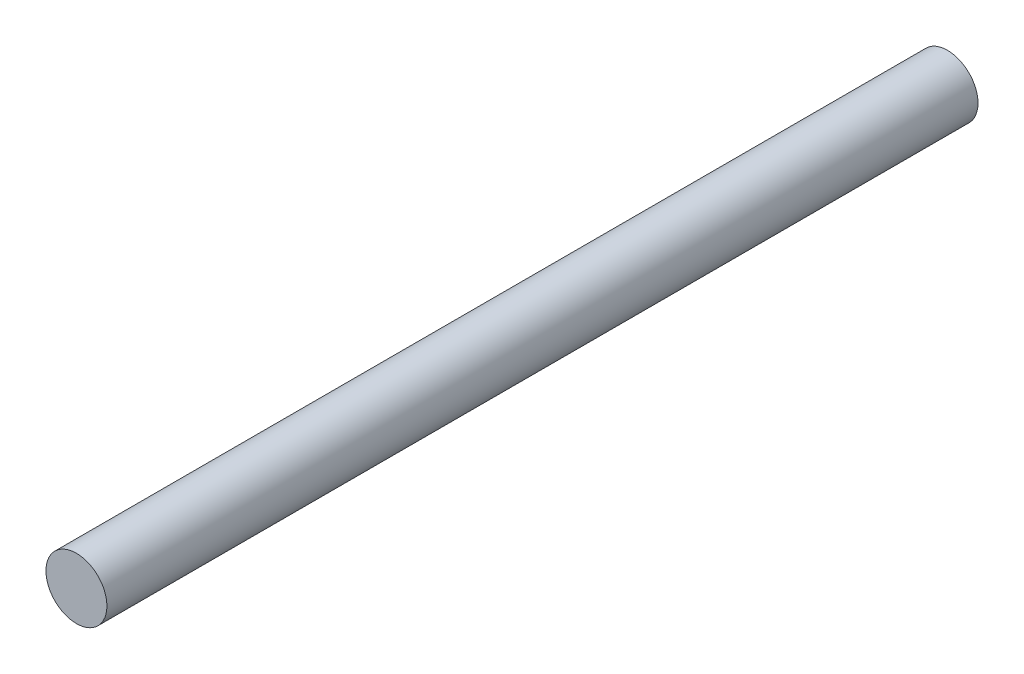
SolidWorks part; units mm, degrees
ref_plane "Front Plane" through (0, 0, 0) normal (0, 0, 1) x (1, 0, 0)
ref_plane "Top Plane" through (0, 0, 0) normal (0, 1, 0) x (1, 0, 0)
ref_plane "Right Plane" through (0, 0, 0) normal (1, 0, 0) x (0, 0, -1)
sketch "Sketch1" plane through (0, 0, 0) normal (0, 0, 1) x (1, 0, 0)
  circle A0 centre (0, 0) radius 17.5
  dimension "D1" = 35
extrude "Boss-Extrude1" add sketch "Sketch1" against normal blind 500
sketch "Sketch3" plane through (0, 0, 0) normal (0, 1, 0) x (1, 0, 0)
  line L0 (13, 500) -> (13, 440)
  line L1 (17.5, 500) -> (-17.5, 500) construction
  line L2 (13, 440) -> (0, 440)
  line L3 (0, -19.25) -> (0, 19.25) construction
  line L4 (0, 440) -> (0, 500)
  line L5 (0, 500) -> (13, 500)
  line L6 (0, 500) -> (0, 531.9153) construction
  dimension "D1" = 26
  dimension "D2" = 60
revolve "Cut-Revolve1" cut sketch "Sketch3" angle 360 about L6
